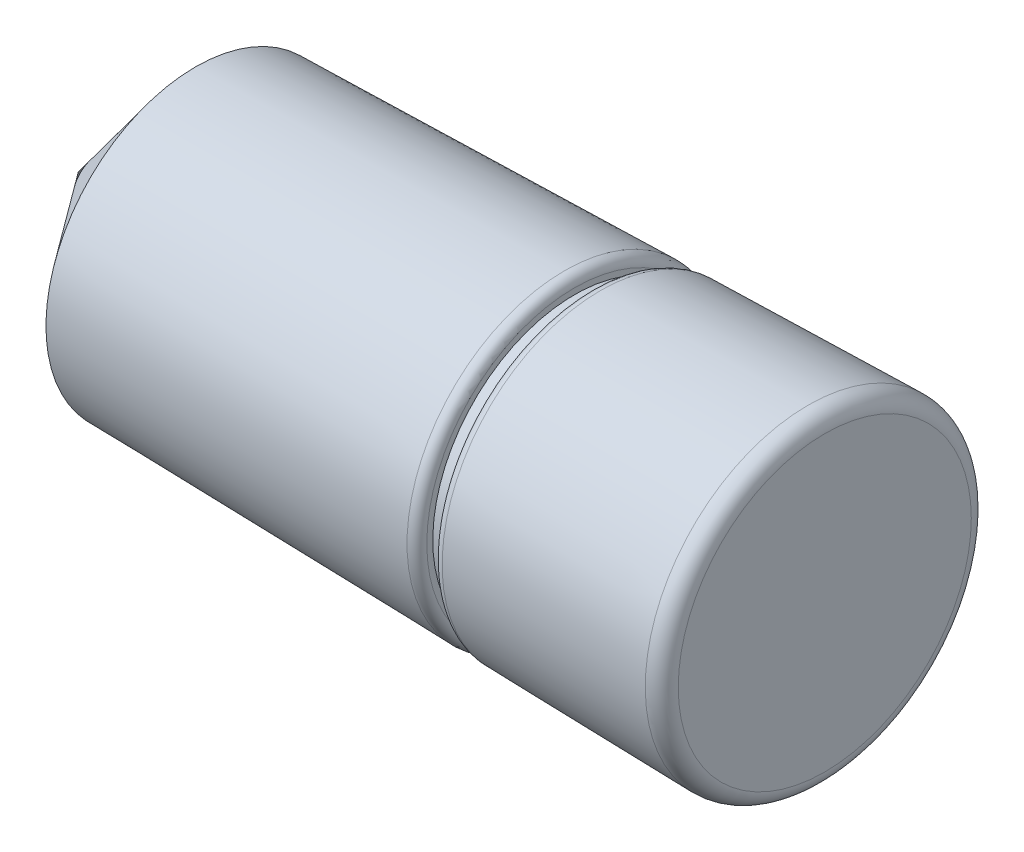
SolidWorks part; units mm, degrees
ref_plane "Front Plane" through (0, 0, 0) normal (0, 0, 1) x (1, 0, 0)
ref_plane "Top Plane" through (0, 0, 0) normal (0, 1, 0) x (1, 0, 0)
ref_plane "Right Plane" through (0, 0, 0) normal (1, 0, 0) x (0, 0, -1)
sketch "Sketch1" plane through (0, 0, 0) normal (0, 0, 1) x (1, 0, 0)
  line L0 (534.156, 153.7174) -> (461.5435, 153.713)
  line L1 (534.156, 163.2394) -> (534.156, 138.7949) construction
  line L2 (512.3413, 138.311) -> (532.5344, 137.8772)
  line L3 (461.5435, 153.713) -> (472.9535, 139.1571)
  line L4 (472.9535, 139.1571) -> (508.8488, 138.386)
  line L5 (534.156, 139.4643) -> (534.156, 153.7174)
  line L6 (474.5094, 153.713) -> (420.505, 153.713) construction
  line L7 (536.696, 136.2549) -> (607.9061, 136.2549) construction
  line L8 (509.8218, 139.3383) -> (509.8218, 139.9185)
  line L9 (509.8218, 139.9185) -> (511.4093, 139.9185)
  line L10 (511.4093, 139.9185) -> (511.4093, 139.2633)
  arc A0 (532.5344, 137.8772) -> (534.156, 139.4643) centre (532.5685, 139.4643) ccw
  arc A1 (511.4093, 139.2633) -> (512.3413, 138.311) centre (512.3618, 139.2633) ccw
  arc A2 (509.8218, 139.3383) -> (508.8488, 138.386) centre (508.8693, 139.3383) cw
  point P13 (534.156, 137.8424)
  point P19 (511.4093, 138.331)
  dimension "D1" = 15.875
  dimension "D3" = 1.5875
  dimension "D6" = 0.9525
  dimension "D2" = 1.5875
  dimension "D4" = 1.5875
  dimension "D5" = 1.5875
revolve "Revolve1" add sketch "Sketch1" angle 360 about L0
